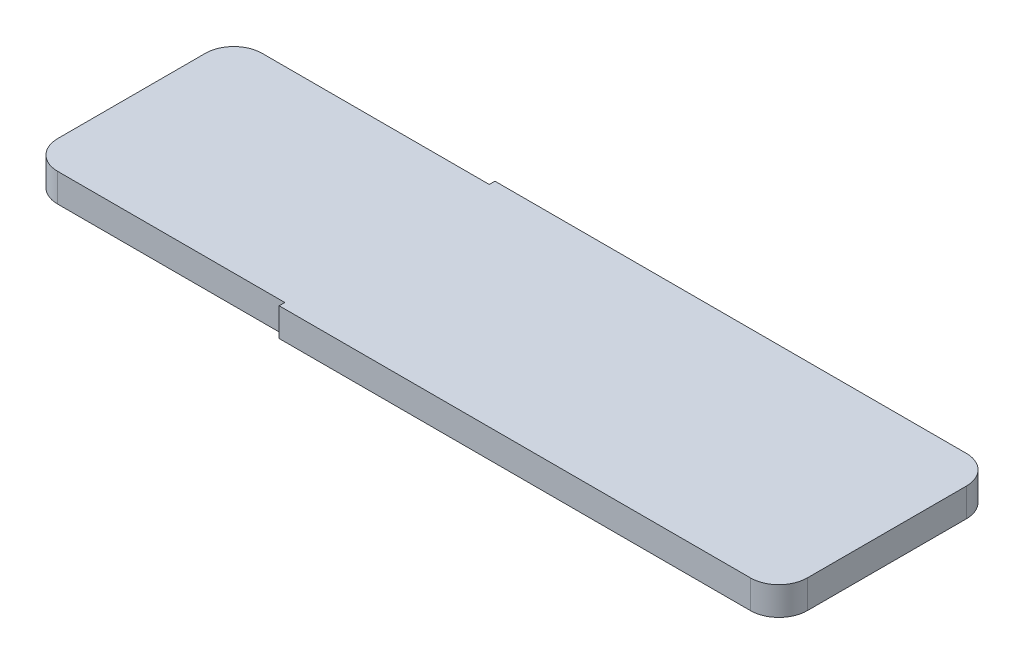
SolidWorks part; units mm, degrees
material "未指定"
ref_plane "正面" through (0, 0, 0) normal (0, 0, 1) x (1, 0, 0)
ref_plane "平面" through (0, 0, 0) normal (0, 1, 0) x (1, 0, 0)
ref_plane "右側面" through (0, 0, 0) normal (1, 0, 0) x (0, 0, -1)
sketch "ｽｹｯﾁ1" plane through (0, 0, 0) normal (0, 1, 0) x (1, 0, 0)
  line L0 (-166, 36) -> (-76, 36)
  line L1 (-76, 36) -> (-76, 38)
  line L2 (-76, 38) -> (100, 38)
  line L3 (100, 38) -> (100, -38)
  line L4 (100, -38) -> (-76, -38)
  line L5 (-76, -38) -> (-76, -36)
  line L6 (-76, -36) -> (-166, -36)
  line L7 (-166, -36) -> (-166, 36)
  line L8 (0, 0) -> (25, 0) construction
  dimension "D1" = 76
  dimension "D2" = 100
  dimension "D3" = 166
  dimension "D4" = 72
  dimension "D5" = 76
extrude "板 外形切り出し" add sketch "ｽｹｯﾁ1" along normal mid plane 10
fillet "外周 角R" radius 10 4 edges at (100, 0, 38) (100, 0, -38) (-166, 0, 36) (-166, 0, -36)
equation "\"ARM_NECK\" = 76"
equation "\"D1@ｽｹｯﾁ1\" = \"ARM_NECK\""
equation "\"ARM_FRONT\" = 100"
equation "\"D2@ｽｹｯﾁ1\" = \"ARM_FRONT\""
equation "\"ARM_BACK\" = 166"
equation "\"D3@ｽｹｯﾁ1\" = \"ARM_BACK\""
equation "\"ARM_STEM_W\" = 36"
equation "\"D4@ｽｹｯﾁ1\" = 2 * ( \"ARM_STEM_W\" )"
equation "\"ARM_HALF_W\" = 38"
equation "\"D5@ｽｹｯﾁ1\" = 2 * ( \"ARM_HALF_W\" )"
equation "\"PLATE_T\" = 10"
equation "\"D1@板 外形切り出し\" = \"PLATE_T\""
equation "\"ARM_R\" = 10"
equation "\"D1@外周 角R\" = \"ARM_R\""
